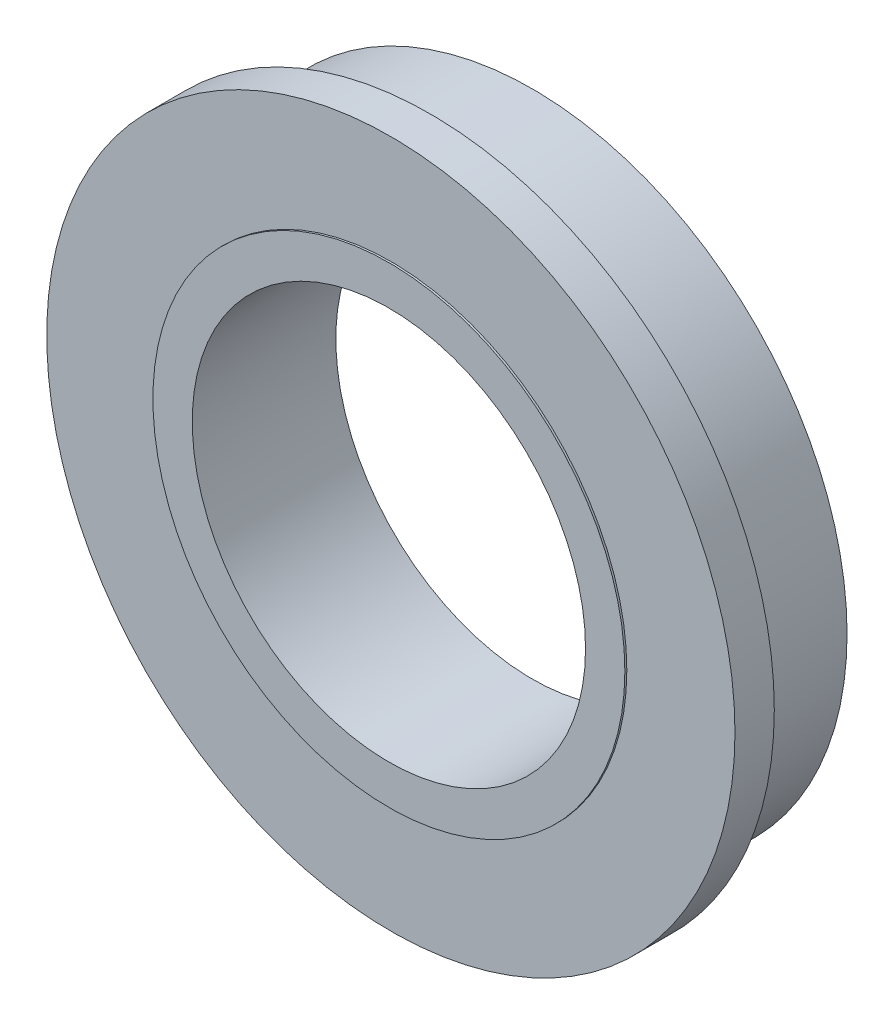
SolidWorks part; units mm, degrees
ref_plane "Front Plane" through (0, 0, 0) normal (0, 0, 1) x (1, 0, 0)
ref_plane "Top Plane" through (0, 0, 0) normal (0, 1, 0) x (1, 0, 0)
ref_plane "Right Plane" through (0, 0, 0) normal (1, 0, 0) x (0, 0, -1)
sketch "Sketch1" plane through (0, 0, 0) normal (0, 0, 1) x (1, 0, 0)
  circle A0 centre (0, 0) radius 10
  circle A1 centre (0, 0) radius 16
  dimension "D1" = 20
  dimension "D2" = 32
extrude "Boss-Extrude1" add sketch "Sketch1" along normal blind 5.2
sketch "Sketch2" plane through (0, 0, 5.2) normal (0, 0, 1) x (1, 0, 0)
  circle A0 centre (0, 0) radius 17.5
  circle A1 centre (0, 0) radius 10
  circle A2 centre (0, 0) radius 10 construction
  dimension "D1" = 35
extrude "Boss-Extrude2" add sketch "Sketch2" along normal blind 2
sketch "Sketch3" plane through (0, 0, 7.2) normal (0, 0, 1) x (1, 0, 0)
  circle A0 centre (0, 0) radius 10
  circle A1 centre (0, 0) radius 12
  circle A2 centre (0, 0) radius 10 construction
  dimension "D1" = 2
extrude "Boss-Extrude3" add sketch "Sketch3" along normal blind 0.1
